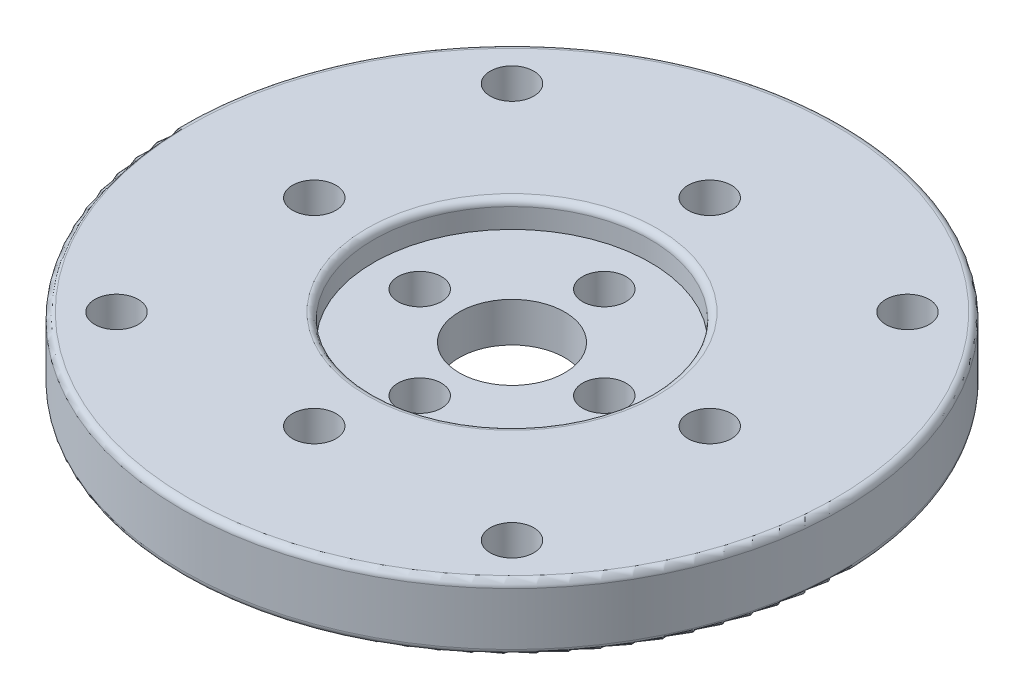
SolidWorks part; units mm, degrees
ref_plane "Front Plane" through (0, 0, 0) normal (0, 0, 1) x (1, 0, 0)
ref_plane "Top Plane" through (0, 0, 0) normal (0, 1, 0) x (1, 0, 0)
ref_plane "Right Plane" through (0, 0, 0) normal (1, 0, 0) x (0, 0, -1)
sketch "Sketch1" plane through (0, 0, 0) normal (0, 1, 0) x (1, 0, 0)
  circle A0 centre (0, 0) radius 4
  circle A1 centre (0, 0) radius 25
  dimension "D1" = 8
  dimension "D2" = 50
extrude "Boss-Extrude1" add sketch "Sketch1" along normal mid plane 5
sketch "Sketch4" plane through (0, 2.5, 0) normal (0, 1, 0) x (1, 0, 0)
  circle A0 centre (0, 0) radius 10.5
  dimension "D1" = 21
extrude "Cut-Extrude3" cut sketch "Sketch4" against normal blind 2
sketch "Sketch2" plane through (0, 2.5, 0) normal (0, 1, 0) x (1, 0, 0)
  circle A3 centre (4.167, 7.534) radius 0.9
  circle A15 centre (0.4226, 7.7385) radius 0.9
  circle A16 centre (-3.3218, 7.943) radius 0.9
  circle A17 centre (-7.534, 4.167) radius 0.9
  circle A18 centre (-7.7385, 0.4226) radius 0.9
  circle A19 centre (-7.943, -3.3218) radius 0.9
  circle A20 centre (-4.167, -7.534) radius 0.9
  circle A21 centre (-0.4226, -7.7385) radius 0.9
  circle A22 centre (3.3218, -7.943) radius 0.9
  circle A23 centre (7.534, -4.167) radius 0.9
  circle A24 centre (7.7385, -0.4226) radius 0.9
  circle A25 centre (7.943, 3.3218) radius 0.9
  dimension "D2" = 1.8
extrude "Cut-Extrude1" [suppressed] cut sketch "Sketch2" against normal up to next contours A25 | A3 | A16 | A15 | A24 | A22 | A21 | A20 | A19 | A18 | A17 | A23
sketch "Sketch3" plane through (0, -2.5, 0) normal (0, -1, 0) x (1, 0, 0)
  line L1 (15, -15) -> (-15, -15) construction
  line L2 (15, -15) -> (15, 15) construction
  line L3 (15, 15) -> (-15, 15) construction
  line L4 (-15, -15) -> (-15, 15) construction
  line L5 (15, -15) -> (-15, 15) construction
  line L6 (15, 15) -> (-15, -15) construction
  circle A0 centre (-15, 15) radius 1.65
  circle A1 centre (15, 15) radius 1.65
  circle A2 centre (15, -15) radius 1.65
  circle A3 centre (-15, -15) radius 1.65
  circle A4 centre (0, 15) radius 1.65
  circle A5 centre (15, 0) radius 1.65
  circle A6 centre (0, -15) radius 1.65
  circle A7 centre (-15, 0) radius 1.65
  point P0 (0, 0)
  dimension "D3" = 3.3
  dimension "D1" = 30
  dimension "D2" = 30
extrude "Cut-Extrude2" cut sketch "Sketch3" against normal up to next
fillet "Fillet1" radius 0.5 3 edges at (0, -2.5, 25) (0, 2.5, 25) (0, 2.5, 10.5)
sketch "Sketch5" plane through (0, 0.5, 0) normal (0, 1, 0) x (1, 0, 0)
  line L0 (-10.5, 0) -> (0, 0) construction
  line L1 (0, 0) -> (0, 10.5) construction
  circle A0 centre (0, 7) radius 1.65
  circle A1 centre (0, -7) radius 1.65
  circle A2 centre (7, 0) radius 1.65
  circle A3 centre (-7, 0) radius 1.65
  circle A4 centre (0, 0) radius 10.5 construction
  circle A5 centre (0, 0) radius 10.5 construction
  point P15 (0, 7.3866)
  point P18 (-7, 0)
  dimension "D1" = 3.3
  dimension "D2" = 14
  dimension "D3" = 14
extrude "Cut-Extrude4" cut sketch "Sketch5" against normal up to next
